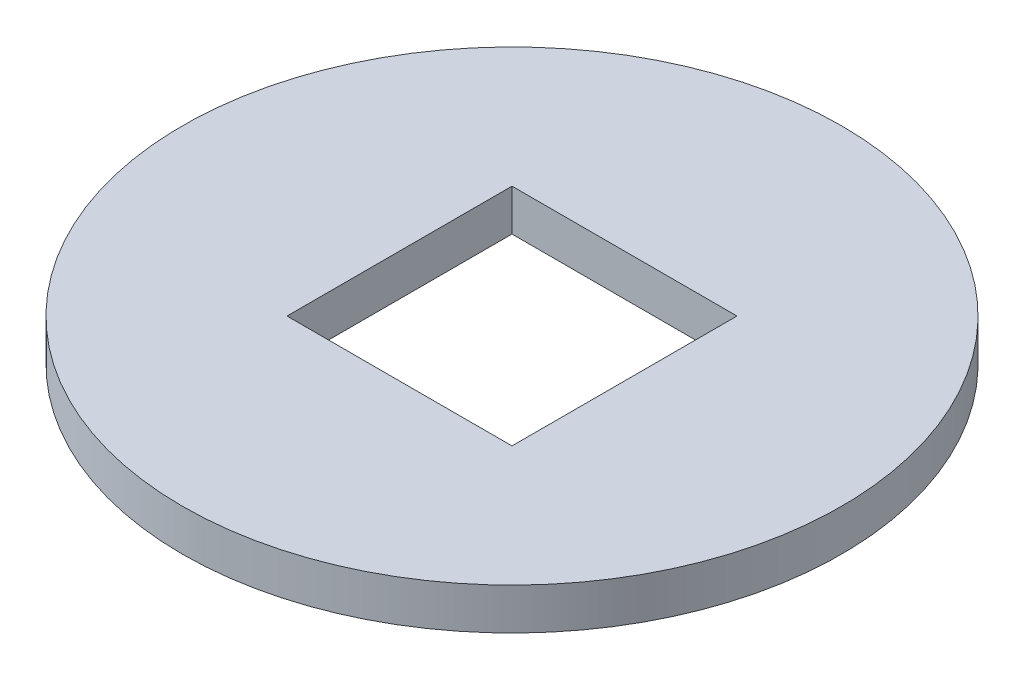
SolidWorks part; units mm, degrees
ref_plane "Front Plane" through (0, 0, 0) normal (0, 0, 1) x (1, 0, 0)
ref_plane "Top Plane" through (0, 0, 0) normal (0, 1, 0) x (1, 0, 0)
ref_plane "Right Plane" through (0, 0, 0) normal (1, 0, 0) x (0, 0, -1)
sketch "Sketch1" plane through (0, 0, 0) normal (0, 1, 0) x (1, 0, 0)
  line L1 (-1.6256, -1.6256) -> (1.6256, -1.6256)
  line L2 (-1.6256, -1.6256) -> (-1.6256, 1.6256)
  line L3 (-1.6256, 1.6256) -> (1.6256, 1.6256)
  line L4 (1.6256, -1.6256) -> (1.6256, 1.6256)
  line L5 (-1.6256, -1.6256) -> (1.6256, 1.6256) construction
  line L6 (-1.6256, 1.6256) -> (1.6256, -1.6256) construction
  circle A0 centre (0, 0) radius 4.7625
  dimension "D1" = 9.525
  dimension "D2" = 3.2512
extrude "Boss-Extrude1" add sketch "Sketch1" along normal blind 0.6
